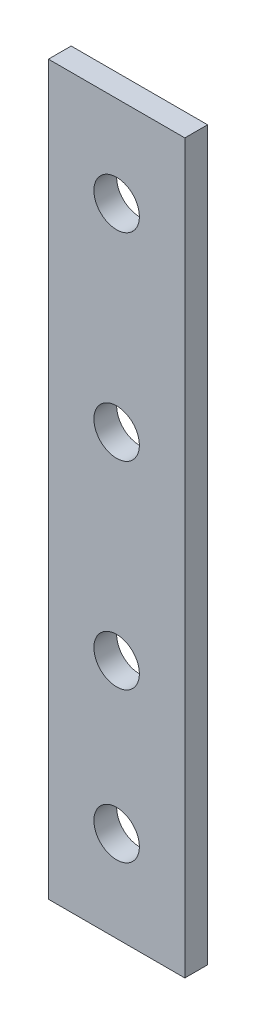
SolidWorks part; units mm, degrees
ref_plane "Front Plane" through (0, 0, 0) normal (0, 0, 1) x (1, 0, 0)
ref_plane "Top Plane" through (0, 0, 0) normal (0, 1, 0) x (1, 0, 0)
ref_plane "Right Plane" through (0, 0, 0) normal (1, 0, 0) x (0, 0, -1)
sketch "Sketch1" plane through (0, 0, 0) normal (0, 0, 1) x (1, 0, 0)
  line L0 (0, 0) -> (0, 101.6)
  line L1 (0, 101.6) -> (19.05, 101.6)
  line L2 (19.05, 101.6) -> (19.05, 0)
  line L3 (19.05, 0) -> (0, 0)
  line L4 (19.05, 50.8) -> (9.525, 50.8) construction
  line L5 (9.525, 50.8) -> (9.525, 88.9) construction
  line L6 (9.525, 88.9) -> (9.525, 33.6169) construction
  line L7 (9.525, 0) -> (9.525, 12.7)
  line L8 (9.525, 33.6169) -> (9.525, 12.7) construction
  circle A0 centre (9.525, 88.9) radius 3.175
  circle A1 centre (9.525, 33.6169) radius 3.175
  circle A2 centre (9.525, 61.2585) radius 3.175
  circle A3 centre (9.525, 12.7) radius 3.175
  dimension "D4" = 38.1
  dimension "D5" = 6.35
  dimension "D7" = 6.35
  dimension "D8" = 6.35
  dimension "D10" = 6.35
  dimension "D1" = 101.6
  dimension "D2" = 19.05
  dimension "D3" = 9.525
  dimension "D6" = 55.2831
  dimension "D9" = 12.7
  dimension "D11" = 20.9169
  dimension "D12" = 48.5585
extrude "Boss-Extrude1" add sketch "Sketch1" along normal blind 3.175
